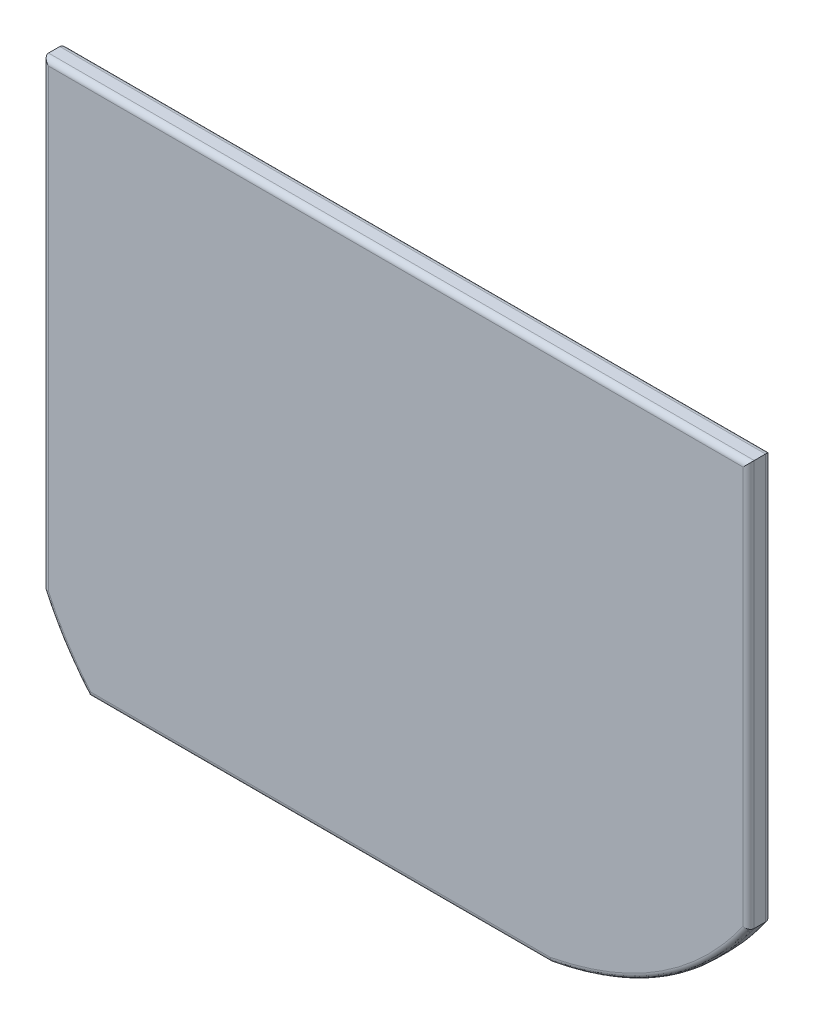
SolidWorks part; units mm, degrees
ref_plane "Front Plane" through (0, 0, 0) normal (0, 0, 1) x (1, 0, 0)
ref_plane "Top Plane" through (0, 0, 0) normal (0, 1, 0) x (1, 0, 0)
ref_plane "Right Plane" through (0, 0, 0) normal (1, 0, 0) x (0, 0, -1)
sketch "Sketch1" plane through (0, 0, 0) normal (0, 0, 1) x (1, 0, 0)
  line L1 (-146, 90.15) -> (-83.413, 90.15)
  line L2 (-146, 90.15) -> (-146, 49.2037)
  line L3 (-141.9813, 42.9489) -> (-100.9647, 42.9489)
  line L4 (-83.413, 90.15) -> (-83.413, 54.2106)
  spline S0 degree 2 poles (-100.9647, 42.9489) (-89.7941, 45.0907) (-83.413, 54.2106) knots 0 0 0 1 1 1
  spline S1 degree 2 poles (-146, 49.2037) (-144.4518, 45.7895) (-141.9813, 42.9489) knots 0 0 0 1 1 1
  dimension "D1" = 62.587
extrude "Boss-Extrude1" add sketch "Sketch1" along normal blind 2
fillet "Fillet1" radius 0.5 12 edges at (-114.7065, 90.15, 2) (-114.7065, 90.15, 0) (-121.473, 42.9489, 0) (-83.413, 72.1803, 0) (-146, 69.6769, 0) (-83.413, 72.1803, 2) (-121.473, 42.9489, 2) (-146, 69.6769, 2)
